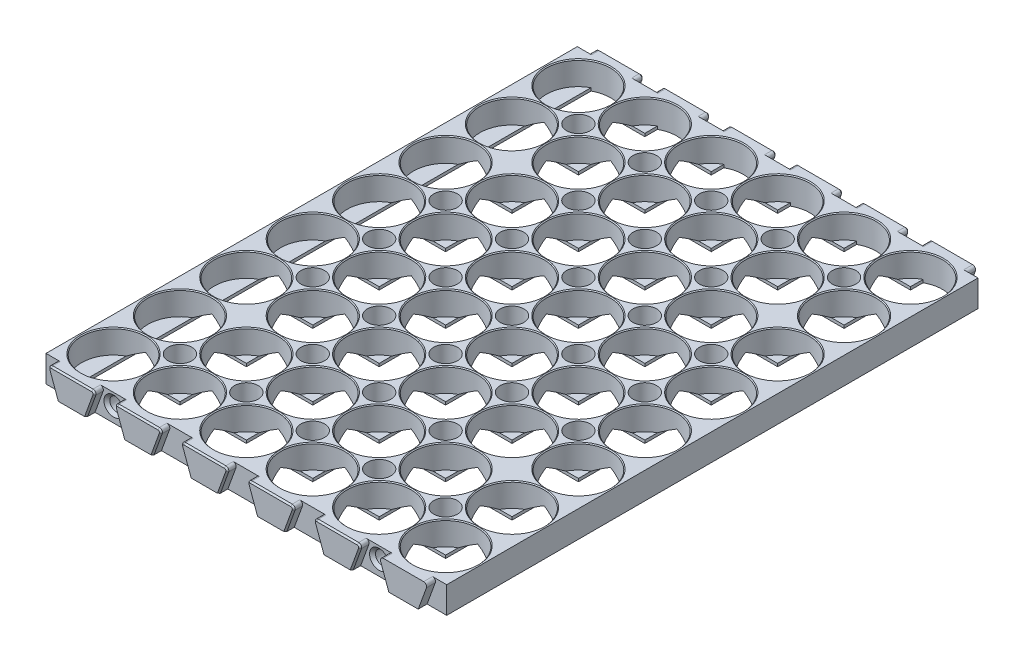
SolidWorks part; units mm, degrees
ref_plane "Front Plane" through (0, 0, 0) normal (0, 0, 1) x (1, 0, 0)
ref_plane "Top Plane" through (0, 0, 0) normal (0, 1, 0) x (1, 0, 0)
ref_plane "Right Plane" through (0, 0, 0) normal (1, 0, 0) x (0, 0, -1)
sketch "Sketch1" plane through (0, 0, 0) normal (0, 1, 0) x (1, 0, 0)
  line L0 (-11.25, 10.875) -> (11.25, 10.875) construction
  line L1 (-11.25, -11.25) -> (11.25, -11.25)
  line L2 (-11.25, -11.25) -> (-11.25, 11.25)
  line L3 (-11.25, 11.25) -> (11.25, 11.25)
  line L4 (11.25, -11.25) -> (11.25, 11.25)
  line L5 (-11.25, -11.25) -> (11.25, 11.25) construction
  line L6 (-11.25, 11.25) -> (11.25, -11.25) construction
  circle A0 centre (0, 0) radius 10.875
  point P0 (0, 0)
  dimension "D1" = 21.75
  dimension "D2" = 22.5
  dimension "D3" = 0.375
extrude "Boss-Extrude1" add sketch "Sketch1" along normal blind 8
sketch "Sketch2" plane through (0, 0, 0) normal (0, -1, 0) x (1, 0, 0)
  line L0 (5.25, 11.25) -> (-5.25, 11.25) construction
  line L1 (11.25, 11.25) -> (5.25, 11.25)
  line L2 (11.25, 11.25) -> (11.25, 5.25)
  line L3 (11.25, 5.25) -> (5.25, 5.25)
  line L4 (5.25, 11.25) -> (5.25, 5.25)
  line L5 (11.25, -11.25) -> (5.25, -11.25)
  line L6 (11.25, -11.25) -> (11.25, -5.25)
  line L7 (11.25, -5.25) -> (5.25, -5.25)
  line L8 (5.25, -11.25) -> (5.25, -5.25)
  line L9 (-11.25, -11.25) -> (-5.25, -11.25)
  line L10 (-11.25, -11.25) -> (-11.25, -5.25)
  line L11 (-11.25, -5.25) -> (-5.25, -5.25)
  line L12 (-5.25, -11.25) -> (-5.25, -5.25)
  line L13 (-11.25, 11.25) -> (-5.25, 11.25)
  line L14 (-11.25, 11.25) -> (-11.25, 5.25)
  line L15 (-11.25, 5.25) -> (-5.25, 5.25)
  line L16 (-5.25, 11.25) -> (-5.25, 5.25)
  line L17 (11.25, 5.25) -> (11.25, -5.25) construction
  line L18 (5.25, -11.25) -> (-5.25, -11.25) construction
  line L19 (-11.25, 5.25) -> (-11.25, -5.25) construction
  dimension "D1" = 10.5
extrude "Boss-Extrude2" add sketch "Sketch2" along normal blind 1
chamfer "Chamfer2" distance 0.3 angle 45 1 edges at (0, 8, 10.875)
pattern_linear "LPattern1" count 8 spacing 22.5 along (0, 0, 1) count 6 spacing 22.5 along (1, 0, 0) of "Boss-Extrude2", "Boss-Extrude1", "Chamfer2"
sketch "Sketch5" plane through (0, 0, -5.25) normal (0, 0, 1) x (1, 0, 0)
  line L25 (-5.25, -1) -> (-5.25, 0) construction
  line L26 (-5.25, -1) -> (-11.25, -1) construction
  line L27 (-11.25, -1) -> (-11.25, 0) construction
  line L29 (-5.25, 0) -> (-9.5238, 0) construction
  line L35 (-5.25, -1) -> (-5.25, 0)
  line L36 (-5.25, -1) -> (-11.25, -1)
  line L37 (-11.25, -1) -> (-11.25, 0)
  line L39 (-5.25, 0) -> (-11.25, 0)
  line L59 (123.75, -1) -> (117.75, -1)
  line L60 (123.75, -1) -> (123.75, 0)
  line L61 (123.75, 0) -> (117.75, 0)
  line L62 (117.75, -1) -> (117.75, 0)
  dimension "D1" = 6
extrude "Boss-Extrude3" add sketch "Sketch5" along normal up to surface (174 mm away)
sketch "Sketch6" plane through (0, 0, 0) normal (0, -1, 0) x (1, 0, 0)
  line L27 (39.75, -11.25) -> (50.25, -11.25) construction
  line L28 (50.25, -11.25) -> (50.25, -9.5238) construction
  line L29 (39.75, -9.5238) -> (39.75, -11.25) construction
  line L30 (17.25, -9.5238) -> (17.25, -11.25) construction
  line L31 (17.25, -11.25) -> (27.75, -11.25) construction
  line L32 (27.75, -11.25) -> (27.75, -9.5238) construction
  line L33 (-5.25, -9.5238) -> (-5.25, -11.25) construction
  line L34 (-5.25, -11.25) -> (5.25, -11.25) construction
  line L35 (5.25, -11.25) -> (5.25, -9.5238) construction
  line L51 (39.75, -11.25) -> (50.25, -11.25)
  line L52 (50.25, -11.25) -> (50.25, -9.5238)
  line L53 (39.75, -9.5238) -> (39.75, -11.25)
  line L54 (17.25, -9.5238) -> (17.25, -11.25)
  line L55 (17.25, -11.25) -> (27.75, -11.25)
  line L56 (27.75, -11.25) -> (27.75, -9.5238)
  line L57 (-5.25, -9.5238) -> (-5.25, -11.25)
  line L58 (-5.25, -11.25) -> (5.25, -11.25)
  line L59 (5.25, -11.25) -> (5.25, -9.5238)
  line L84 (5.25, 168.75) -> (-5.25, 168.75) construction
  line L85 (-5.25, 168.75) -> (-5.25, 167.0238) construction
  line L86 (5.25, 167.0238) -> (5.25, 168.75) construction
  line L87 (27.75, 167.0238) -> (27.75, 168.75) construction
  line L88 (27.75, 168.75) -> (17.25, 168.75) construction
  line L89 (17.25, 168.75) -> (17.25, 167.0238) construction
  line L93 (50.25, 167.0238) -> (50.25, 168.75) construction
  line L94 (50.25, 168.75) -> (39.75, 168.75) construction
  line L95 (39.75, 168.75) -> (39.75, 167.0238) construction
  line L96 (5.25, 168.75) -> (-5.25, 168.75)
  line L97 (-5.25, 168.75) -> (-5.25, 167.0238)
  line L98 (5.25, 167.0238) -> (5.25, 168.75)
  line L99 (27.75, 167.0238) -> (27.75, 168.75)
  line L100 (27.75, 168.75) -> (17.25, 168.75)
  line L101 (17.25, 168.75) -> (17.25, 167.0238)
  line L105 (50.25, 167.0238) -> (50.25, 168.75)
  line L106 (50.25, 168.75) -> (39.75, 168.75)
  line L107 (39.75, 168.75) -> (39.75, 167.0238)
  line L114 (72.75, 167.0238) -> (72.75, 168.75) construction
  line L115 (72.75, 168.75) -> (62.25, 168.75) construction
  line L116 (62.25, 168.75) -> (62.25, 167.0238) construction
  line L123 (72.75, 167.0238) -> (72.75, 168.75)
  line L124 (72.75, 168.75) -> (62.25, 168.75)
  line L125 (62.25, 168.75) -> (62.25, 167.0238)
  line L126 (117.75, 167.0238) -> (117.75, 168.75) construction
  line L127 (117.75, 168.75) -> (107.25, 168.75) construction
  line L128 (107.25, 168.75) -> (107.25, 167.0238) construction
  line L129 (62.25, -11.25) -> (72.75, -11.25)
  line L130 (72.75, -11.25) -> (72.75, -9.5238)
  line L131 (62.25, -9.5238) -> (62.25, -11.25)
  line L132 (62.25, -11.25) -> (72.75, -11.25)
  line L133 (72.75, -11.25) -> (72.75, -9.5238)
  line L134 (62.25, -9.5238) -> (62.25, -11.25)
  line L135 (95.25, 167.0238) -> (95.25, 168.75) construction
  line L136 (95.25, 168.75) -> (84.75, 168.75) construction
  line L137 (84.75, 168.75) -> (84.75, 167.0238) construction
  line L138 (107.25, -11.25) -> (117.75, -11.25) construction
  line L139 (117.75, -11.25) -> (117.75, -9.5238) construction
  line L140 (107.25, -9.5238) -> (107.25, -11.25) construction
  line L141 (84.75, -11.25) -> (95.25, -11.25) construction
  line L142 (95.25, -11.25) -> (95.25, -9.5238) construction
  line L143 (84.75, -9.5238) -> (84.75, -11.25) construction
  line L144 (117.75, 167.0238) -> (117.75, 168.75)
  line L145 (117.75, 168.75) -> (107.25, 168.75)
  line L146 (107.25, 168.75) -> (107.25, 167.0238)
  line L147 (95.25, 167.0238) -> (95.25, 168.75)
  line L148 (95.25, 168.75) -> (84.75, 168.75)
  line L149 (84.75, 168.75) -> (84.75, 167.0238)
  line L150 (107.25, -11.25) -> (117.75, -11.25)
  line L151 (117.75, -11.25) -> (117.75, -9.5238)
  line L152 (107.25, -9.5238) -> (107.25, -11.25)
  line L153 (84.75, -11.25) -> (95.25, -11.25)
  line L154 (95.25, -11.25) -> (95.25, -9.5238)
  line L155 (84.75, -9.5238) -> (84.75, -11.25)
  arc A9 (39.75, -9.5238) -> (50.25, -9.5238) centre (45, 0) ccw construction
  arc A10 (17.25, -9.5238) -> (27.75, -9.5238) centre (22.5, 0) ccw construction
  arc A11 (-5.25, -9.5238) -> (5.25, -9.5238) centre (0, 0) ccw construction
  arc A17 (39.75, -9.5238) -> (50.25, -9.5238) centre (45, 0) ccw
  arc A18 (17.25, -9.5238) -> (27.75, -9.5238) centre (22.5, 0) ccw
  arc A19 (-5.25, -9.5238) -> (5.25, -9.5238) centre (0, 0) ccw
  arc A28 (5.25, 167.0238) -> (-5.25, 167.0238) centre (0, 157.5) ccw construction
  arc A29 (27.75, 167.0238) -> (17.25, 167.0238) centre (22.5, 157.5) ccw construction
  arc A31 (50.25, 167.0238) -> (39.75, 167.0238) centre (45, 157.5) ccw construction
  arc A32 (5.25, 167.0238) -> (-5.25, 167.0238) centre (0, 157.5) ccw
  arc A33 (27.75, 167.0238) -> (17.25, 167.0238) centre (22.5, 157.5) ccw
  arc A35 (50.25, 167.0238) -> (39.75, 167.0238) centre (45, 157.5) ccw
  arc A38 (72.75, 167.0238) -> (62.25, 167.0238) centre (67.5, 157.5) ccw construction
  arc A41 (72.75, 167.0238) -> (62.25, 167.0238) centre (67.5, 157.5) ccw
  arc A42 (117.75, 167.0238) -> (107.25, 167.0238) centre (112.5, 157.5) ccw construction
  arc A43 (62.25, -9.5238) -> (72.75, -9.5238) centre (67.5, 0) ccw
  arc A44 (62.25, -9.5238) -> (72.75, -9.5238) centre (67.5, 0) ccw
  arc A45 (95.25, 167.0238) -> (84.75, 167.0238) centre (90, 157.5) ccw construction
  arc A46 (107.25, -9.5238) -> (117.75, -9.5238) centre (112.5, 0) ccw construction
  arc A47 (84.75, -9.5238) -> (95.25, -9.5238) centre (90, 0) ccw construction
  arc A48 (117.75, 167.0238) -> (107.25, 167.0238) centre (112.5, 157.5) ccw
  arc A49 (95.25, 167.0238) -> (84.75, 167.0238) centre (90, 157.5) ccw
  arc A50 (107.25, -9.5238) -> (117.75, -9.5238) centre (112.5, 0) ccw
  arc A51 (84.75, -9.5238) -> (95.25, -9.5238) centre (90, 0) ccw
  dimension "D1" = 0
extrude "Boss-Extrude4" add sketch "Sketch6" along normal up to surface (1 mm away) up to face at (-8.25, -1, 78.75)
sketch "Sketch7" plane through (0, 0, 0) normal (0, 0, 1) x (1, 0, 0)
  line L0 (-11.25, 8) -> (123.75, 8) construction
  line L1 (-5.25, 0) -> (5.25, 0)
  line L2 (-5.25, 0) -> (0, 5.25) construction
  line L3 (0, 5.25) -> (5.25, 0) construction
  line L4 (0, 0) -> (0, 8) construction
  line L5 (84.75, 0) -> (90, 3.0311)
  line L6 (-5.25, 0) -> (0, 3.0311)
  line L7 (0, 3.0311) -> (5.25, 0)
  line L8 (90, 3.0311) -> (95.25, 0)
  line L9 (-5.25, -1) -> (-5.25, 0) construction
  line L10 (5.25, -1) -> (5.25, 0) construction
  line L11 (-5.25, -1) -> (-5.25, 0) construction
  line L12 (5.25, -1) -> (5.25, 0) construction
  line L13 (17.25, 0) -> (22.5, 3.0311)
  line L14 (22.5, 3.0311) -> (27.75, 0)
  line L15 (17.25, 0) -> (27.75, 0)
  line L16 (39.75, 0) -> (45, 3.0311)
  line L17 (45, 3.0311) -> (50.25, 0)
  line L18 (39.75, 0) -> (50.25, 0)
  line L19 (62.25, 0) -> (67.5, 3.0311)
  line L20 (67.5, 3.0311) -> (72.75, 0)
  line L21 (62.25, 0) -> (72.75, 0)
  line L22 (-5.25, 0) -> (17.25, 0) construction
  line L23 (84.75, 0) -> (95.25, 0)
  line L24 (107.25, 0) -> (112.5, 3.0311)
  line L25 (112.5, 3.0311) -> (117.75, 0)
  line L26 (107.25, 0) -> (117.75, 0)
  dimension "D1" = 45
  dimension "D2" = 30
  dimension "D3" = 4.9689
  dimension "D5" = 22.5
  dimension "D4" = 6
extrude "Cut-Extrude1" cut sketch "Sketch7" along normal up to surface (162.75 mm away) up to face at (56.25, -0.3333, 162.75)
sketch "Sketch16" plane through (0, 0, 0) normal (1, 0, 0) x (0, 0, -1)
  line L2 (-5.25, -1) -> (-5.25, 0) construction
  line L3 (5.25, -1) -> (5.25, 0) construction
  line L4 (-5.25, 0) -> (0, 3.0311)
  line L5 (0, 3.0311) -> (5.25, 0)
  line L6 (-5.25, 0) -> (5.25, 0)
  line L7 (-5.25, -1) -> (-5.25, 0) construction
  line L8 (5.25, -1) -> (5.25, 0) construction
  line L9 (-22.5, 3.0311) -> (-17.25, 0)
  line L10 (-27.75, 0) -> (-17.25, 0)
  line L11 (-27.75, 0) -> (-22.5, 3.0311)
  line L12 (-45, 3.0311) -> (-39.75, 0)
  line L13 (-50.25, 0) -> (-39.75, 0)
  line L14 (-50.25, 0) -> (-45, 3.0311)
  line L15 (-67.5, 3.0311) -> (-62.25, 0)
  line L16 (-72.75, 0) -> (-62.25, 0)
  line L17 (-72.75, 0) -> (-67.5, 3.0311)
  line L18 (-90, 3.0311) -> (-84.75, 0)
  line L19 (-95.25, 0) -> (-84.75, 0)
  line L20 (-95.25, 0) -> (-90, 3.0311)
  line L21 (-112.5, 3.0311) -> (-107.25, 0)
  line L22 (-117.75, 0) -> (-107.25, 0)
  line L23 (-117.75, 0) -> (-112.5, 3.0311)
  line L24 (-135, 3.0311) -> (-129.75, 0)
  line L25 (-140.25, 0) -> (-129.75, 0)
  line L26 (-140.25, 0) -> (-135, 3.0311)
  line L27 (-157.5, 3.0311) -> (-152.25, 0)
  line L28 (-162.75, 0) -> (-152.25, 0)
  line L29 (-162.75, 0) -> (-157.5, 3.0311)
  line L42 (0, 3.0311) -> (-22.5, 3.0311) construction
  dimension "D1" = 30
  dimension "D3" = 22.5
  dimension "D2" = 8
extrude "Cut-Extrude7" cut sketch "Sketch16" along normal up to surface (107.25 mm away)
sketch "Sketch8" plane through (0, 0, -11.25) normal (0, 0, -1) x (-1, 0, 0)
  line L0 (0, -1) -> (0, 8) construction
  line L1 (-27.4743, -1) -> (-30.75, 8)
  line L2 (-123.75, 8) -> (11.25, 8) construction
  line L3 (4.9743, -1) -> (-4.9743, -1)
  line L4 (-4.9743, -1) -> (-8.25, 8)
  line L5 (-8.25, 8) -> (8.25, 8)
  line L6 (4.9743, -1) -> (8.25, 8)
  line L7 (11.25, 8) -> (11.25, -1) construction
  line L8 (11.25, -1) -> (-123.75, -1) construction
  line L9 (-30.75, 8) -> (-14.25, 8)
  line L10 (-123.75, 8) -> (11.25, 8) construction
  line L11 (-17.5257, -1) -> (-14.25, 8)
  line L12 (-17.5257, -1) -> (-27.4743, -1)
  line L13 (-49.9743, -1) -> (-53.25, 8)
  line L14 (-53.25, 8) -> (-36.75, 8)
  line L15 (-40.0257, -1) -> (-36.75, 8)
  line L16 (-40.0257, -1) -> (-49.9743, -1)
  line L17 (-72.4743, -1) -> (-75.75, 8)
  line L18 (-75.75, 8) -> (-59.25, 8)
  line L19 (-62.5257, -1) -> (-59.25, 8)
  line L20 (-62.5257, -1) -> (-72.4743, -1)
  line L21 (-4.9743, -1) -> (-27.4743, -1) construction
  line L22 (-123.75, 8) -> (11.25, 8) construction
  line L23 (-94.9743, -1) -> (-98.25, 8)
  line L24 (-98.25, 8) -> (-81.75, 8)
  line L25 (-85.0257, -1) -> (-81.75, 8)
  line L26 (-85.0257, -1) -> (-94.9743, -1)
  line L27 (-117.4743, -1) -> (-120.75, 8)
  line L28 (-120.75, 8) -> (-104.25, 8)
  line L29 (-107.5257, -1) -> (-104.25, 8)
  line L30 (-107.5257, -1) -> (-117.4743, -1)
  dimension "D1" = 70
  dimension "D2" = 3
  dimension "D4" = 22.5
  dimension "D5" = 9
  dimension "D3" = 6
sketch "Sketch9" plane through (0, 0, 168.75) normal (0, 0, 1) x (1, 0, 0)
  line L0 (85.0257, -1) -> (94.9743, -1) construction
  line L3 (85.0257, -1) -> (81.75, 8) construction
  line L20 (94.9743, -1) -> (98.25, 8) construction
  line L21 (98.25, 8) -> (81.75, 8) construction
  line L22 (85.0257, -1) -> (94.9743, -1)
  line L23 (85.0257, -1) -> (81.75, 8)
  line L24 (-4.9743, -1) -> (4.9743, -1)
  line L25 (4.9743, -1) -> (8.25, 8)
  line L26 (8.25, 8) -> (-8.25, 8)
  line L27 (-8.25, 8) -> (-4.9743, -1)
  line L28 (-4.9743, -1) -> (4.9743, -1)
  line L29 (4.9743, -1) -> (8.25, 8)
  line L30 (8.25, 8) -> (-8.25, 8)
  line L31 (-8.25, 8) -> (-4.9743, -1)
  line L32 (72.4743, -1) -> (75.75, 8)
  line L33 (75.75, 8) -> (59.25, 8)
  line L34 (59.25, 8) -> (62.5257, -1)
  line L35 (62.5257, -1) -> (72.4743, -1)
  line L36 (72.4743, -1) -> (75.75, 8)
  line L37 (75.75, 8) -> (59.25, 8)
  line L38 (59.25, 8) -> (62.5257, -1)
  line L39 (62.5257, -1) -> (72.4743, -1)
  line L40 (49.9743, -1) -> (53.25, 8)
  line L41 (53.25, 8) -> (36.75, 8)
  line L42 (36.75, 8) -> (40.0257, -1)
  line L43 (40.0257, -1) -> (49.9743, -1)
  line L44 (49.9743, -1) -> (53.25, 8)
  line L45 (53.25, 8) -> (36.75, 8)
  line L46 (36.75, 8) -> (40.0257, -1)
  line L47 (40.0257, -1) -> (49.9743, -1)
  line L48 (14.25, 8) -> (17.5257, -1)
  line L49 (17.5257, -1) -> (27.4743, -1)
  line L50 (27.4743, -1) -> (30.75, 8)
  line L51 (30.75, 8) -> (14.25, 8)
  line L52 (14.25, 8) -> (17.5257, -1)
  line L53 (17.5257, -1) -> (27.4743, -1)
  line L54 (27.4743, -1) -> (30.75, 8)
  line L55 (30.75, 8) -> (14.25, 8)
  line L56 (94.9743, -1) -> (98.25, 8)
  line L57 (98.25, 8) -> (81.75, 8)
  line L58 (107.5257, -1) -> (117.4743, -1) construction
  line L59 (107.5257, -1) -> (104.25, 8) construction
  line L60 (117.4743, -1) -> (120.75, 8) construction
  line L61 (120.75, 8) -> (104.25, 8) construction
  line L62 (107.5257, -1) -> (117.4743, -1)
  line L63 (107.5257, -1) -> (104.25, 8)
  line L64 (117.4743, -1) -> (120.75, 8)
  line L65 (120.75, 8) -> (104.25, 8)
  dimension "D1" = 0
  dimension "D2" = 0
  dimension "D3" = 0
  dimension "D4" = 0
extrude "Boss-Extrude5" add sketch "Sketch8" along normal blind 3
extrude "Boss-Extrude6" add sketch "Sketch9" along normal blind 3
fillet "Fillet1" radius 1 24 edges at (-8.25, 8, -12.75) (8.25, 8, -12.75) (14.25, 8, -12.75) (59.25, 8, -12.75) (53.25, 8, -12.75) (30.75, 8, -12.75) (36.75, 8, -12.75) (75.75, 8, -12.75) (81.75, 8, -12.75) (98.25, 8, -12.75) (104.25, 8, -12.75) (120.75, 8, -12.75) (-8.25, 8, 170.25) (8.25, 8, 170.25) (14.25, 8, 170.25) (30.75, 8, 170.25) (36.75, 8, 170.25) (53.25, 8, 170.25) (59.25, 8, 170.25) (75.75, 8, 170.25) (81.75, 8, 170.25) (98.25, 8, 170.25) (104.25, 8, 170.25) (120.75, 8, 170.25)
chamfer "Chamfer3" distance 0.5 angle 45 50 edges at (6.3679, 2.829, -14.25) (0, 8, -14.25) (-6.3679, 2.829, -14.25) (73.8679, 2.829, -14.25) (67.5, 8, -14.25) (61.1321, 2.829, -14.25) (51.3679, 2.829, -14.25) (45, 8, -14.25) (38.6321, 2.829, -14.25) (28.8679, 2.829, -14.25) (22.5, 8, -14.25) (16.1321, 2.829, -14.25) (73.8679, 2.829, 171.75) (61.1321, 2.829, 171.75) (67.5, 8, 171.75) (51.3679, 2.829, 171.75) (38.6321, 2.829, 171.75) (45, 8, 171.75) (28.8679, 2.829, 171.75) (16.1321, 2.829, 171.75) (22.5, 8, 171.75) (6.3679, 2.829, 171.75) (-6.3679, 2.829, 171.75) (0, 8, 171.75) (83.6321, 2.829, -14.25) (90, 8, -14.25) (96.3679, 2.829, -14.25) (96.3679, 2.829, 171.75) (90, 8, 171.75) (83.6321, 2.829, 171.75) (82.359, 7.5736, -14.25) (97.641, 7.5736, -14.25) (97.641, 7.5736, 171.75) (82.359, 7.5736, 171.75) (75.141, 7.5736, 171.75) (59.859, 7.5736, 171.75) (52.641, 7.5736, 171.75) (37.359, 7.5736, 171.75) (30.141, 7.5736, 171.75) (14.859, 7.5736, 171.75) (7.641, 7.5736, 171.75) (-7.641, 7.5736, 171.75) (75.141, 7.5736, -14.25) (59.859, 7.5736, -14.25) (52.641, 7.5736, -14.25) (37.359, 7.5736, -14.25) (30.141, 7.5736, -14.25) (14.859, 7.5736, -14.25) (7.641, 7.5736, -14.25) (-7.641, 7.5736, -14.25)
sketch "Sketch10" plane through (0, 0, -11.25) normal (0, 0, -1) x (-1, 0, 0)
  line L0 (-11.25, -1) -> (-11.25, 8) construction
  line L2 (-4.9743, -1) -> (-17.5257, -1) construction
  line L4 (-14.25, 8) -> (-8.25, 8) construction
  line L5 (-56.25, 8) -> (-56.25, -1) construction
  line L6 (-49.9743, -1) -> (-62.5257, -1) construction
  line L7 (-59.25, 8) -> (-53.25, 8) construction
  circle A0 centre (-11.25, 4) radius 2.25
  circle A1 centre (-101.25, 4) radius 2.25
  dimension "D2" = 4.5
  dimension "D1" = 4
sketch "Sketch11" plane through (0, 0, 168.75) normal (0, 0, 1) x (1, 0, 0)
  circle A0 centre (11.25, 4) radius 2.25 construction
  circle A1 centre (11.25, 4) radius 2.25
  circle A2 centre (101.25, 4) radius 2.25 construction
  circle A3 centre (101.25, 4) radius 2.25
extrude "Cut-Extrude2" cut sketch "Sketch10" against normal blind 5
extrude "Cut-Extrude3" cut sketch "Sketch11" against normal blind 5
chamfer "Chamfer5" distance 1 angle 45 4 edges at (103.5, 4, -11.25) (9, 4, -11.25) (13.5, 4, 168.75) (103.5, 4, 168.75)
sketch "Sketch17" plane through (0, -1, 0) normal (0, -1, 0) x (1, 0, 0)
  line L0 (5.25, 5.25) -> (17.25, 17.25) construction
  line L1 (11.25, 11.25) -> (33.75, 11.25) construction
  line L2 (95.25, 140.25) -> (107.25, 152.25) construction
  line L3 (17.25, 140.25) -> (5.25, 152.25) construction
  circle A0 centre (11.25, 11.25) radius 4
  circle A1 centre (33.75, 11.25) radius 4
  circle A2 centre (56.25, 11.25) radius 4
  circle A33 centre (33.75, 146.25) radius 4 [skipped]
  circle A34 centre (56.25, 146.25) radius 4 [skipped]
  circle A35 centre (33.75, 168.75) radius 4 [skipped]
  circle A36 centre (33.75, 191.25) radius 4 [skipped]
  circle A37 centre (56.25, 191.25) radius 4 [skipped]
  circle A38 centre (33.75, 213.75) radius 4 [skipped]
  circle A39 centre (56.25, 213.75) radius 4 [skipped]
  circle A40 centre (33.75, 236.25) radius 4 [skipped]
  circle A41 centre (56.25, 236.25) radius 4 [skipped]
  circle A42 centre (11.25, 146.25) radius 4 [skipped]
  circle A43 centre (11.25, 191.25) radius 4 [skipped]
  circle A44 centre (11.25, 213.75) radius 4 [skipped]
  circle A45 centre (11.25, 236.25) radius 4 [skipped]
  circle A46 centre (56.25, 168.75) radius 4 construction
  circle A47 centre (11.25, 168.75) radius 4 construction
  circle A48 centre (33.75, 123.75) radius 4 [skipped]
  circle A49 centre (56.25, 123.75) radius 4 [skipped]
  circle A50 centre (11.25, 123.75) radius 4 [skipped]
  circle A57 centre (33.75, 33.75) radius 4 [skipped]
  circle A58 centre (33.75, 56.25) radius 4 [skipped]
  circle A59 centre (56.25, 56.25) radius 4 [skipped]
  circle A60 centre (33.75, 78.75) radius 4 [skipped]
  circle A61 centre (56.25, 78.75) radius 4 [skipped]
  circle A62 centre (33.75, 101.25) radius 4 [skipped]
  circle A63 centre (56.25, 101.25) radius 4 [skipped]
  circle A64 centre (11.25, 56.25) radius 4 [skipped]
  circle A65 centre (11.25, 78.75) radius 4 [skipped]
  circle A66 centre (11.25, 101.25) radius 4 [skipped]
  circle A67 centre (56.25, 33.75) radius 4 construction
  circle A68 centre (11.25, 33.75) radius 4 construction
  circle A69 centre (11.25, 33.75) radius 4 construction
  circle A70 centre (33.75, 33.75) radius 4
  circle A71 centre (56.25, 33.75) radius 4
  circle A72 centre (11.25, 56.25) radius 4
  circle A73 centre (33.75, 56.25) radius 4
  circle A74 centre (56.25, 56.25) radius 4
  circle A75 centre (11.25, 78.75) radius 4
  circle A76 centre (33.75, 78.75) radius 4
  circle A77 centre (56.25, 78.75) radius 4
  circle A78 centre (11.25, 101.25) radius 4
  circle A79 centre (33.75, 101.25) radius 4
  circle A80 centre (56.25, 101.25) radius 4
  circle A81 centre (11.25, 123.75) radius 4 construction
  circle A82 centre (33.75, 123.75) radius 4
  circle A83 centre (56.25, 123.75) radius 4
  circle A84 centre (11.25, 146.25) radius 4
  circle A85 centre (33.75, 146.25) radius 4
  circle A86 centre (56.25, 146.25) radius 4
  circle A87 centre (11.25, 258.75) radius 4 [skipped]
  circle A88 centre (33.75, 258.75) radius 4 [skipped]
  circle A89 centre (56.25, 258.75) radius 4 [skipped]
  circle A90 centre (11.25, 281.25) radius 4 [skipped]
  circle A91 centre (33.75, 281.25) radius 4 [skipped]
  circle A92 centre (56.25, 281.25) radius 4 [skipped]
  circle A93 centre (78.75, 11.25) radius 4
  circle A94 centre (78.75, 33.75) radius 4
  circle A95 centre (78.75, 56.25) radius 4
  circle A96 centre (78.75, 78.75) radius 4
  circle A97 centre (78.75, 101.25) radius 4
  circle A98 centre (78.75, 123.75) radius 4
  circle A99 centre (78.75, 146.25) radius 4
  circle A106 centre (78.75, 168.75) radius 4 [skipped]
  circle A107 centre (78.75, 191.25) radius 4 [skipped]
  circle A108 centre (78.75, 213.75) radius 4 [skipped]
  circle A109 centre (78.75, 236.25) radius 4 [skipped]
  circle A110 centre (78.75, 258.75) radius 4 [skipped]
  circle A111 centre (78.75, 281.25) radius 4 [skipped]
  circle A112 centre (101.25, 11.25) radius 4
  circle A113 centre (101.25, 33.75) radius 4 construction
  circle A114 centre (101.25, 56.25) radius 4
  circle A115 centre (101.25, 78.75) radius 4
  circle A116 centre (101.25, 101.25) radius 4
  circle A117 centre (101.25, 123.75) radius 4 construction
  circle A118 centre (101.25, 146.25) radius 4
  circle A126 centre (101.25, 191.25) radius 4 [skipped]
  circle A127 centre (101.25, 213.75) radius 4 [skipped]
  circle A128 centre (101.25, 236.25) radius 4 [skipped]
  circle A129 centre (101.25, 258.75) radius 4 [skipped]
  circle A130 centre (101.25, 281.25) radius 4 [skipped]
  circle A131 centre (101.25, 168.75) radius 4 [skipped]
  dimension "D4" = 22.5
  dimension "D1" = 8
  dimension "D2" = 5
  dimension "D3" = 13
  dimension "D5" = 7
extrude "Cut-Extrude8" cut sketch "Sketch17" against normal through all
sketch "Sketch18" plane through (0, -1, 0) normal (0, -1, 0) x (1, 0, 0)
  line L0 (123.75, -11.25) -> (123.75, 168.75) construction
  line L1 (107.25, 117.75) -> (107.25, 129.75) construction
  line L2 (5.25, 117.75) -> (17.25, 129.75) construction
  line L3 (5.25, 27.75) -> (17.25, 39.75) construction
  line L4 (95.25, 27.75) -> (107.25, 39.75) construction
  line L7 (95.25, 129.75) -> (95.25, 117.75) construction
  line L8 (107.25, 129.75) -> (95.25, 129.75) construction
  line L38 (123.75, 78.75) -> (-11.25, 78.75) construction
  line L40 (-11.25, 168.75) -> (-11.25, -11.25) construction
  line L42 (95.25, 129.75) -> (107.25, 117.75) construction
  circle A0 centre (11.25, 33.75) radius 2.1
  circle A4 centre (101.25, 33.75) radius 2.1
  circle A7 centre (101.25, 123.75) radius 2.1
  circle A8 centre (11.25, 123.75) radius 2.1
  dimension "D1" = 4.2
extrude "Cut-Extrude9" cut sketch "Sketch18" against normal blind 4
sketch "Sketch19" plane through (0, -1, 0) normal (0, -1, 0) x (1, 0, 0)
  line L0 (123.75, 78.75) -> (-11.25, 78.75) construction
  line L1 (123.75, -11.25) -> (123.75, 168.75) construction
  line L2 (-11.25, 168.75) -> (-11.25, -11.25) construction
  circle A2 centre (101.25, 123.75) radius 1.7
  circle A3 centre (11.25, 33.75) radius 1.7
  circle A4 centre (11.25, 123.75) radius 1.7
  circle A5 centre (101.25, 33.75) radius 1.7
  dimension "D1" = 3.4
extrude "Cut-Extrude10" cut sketch "Sketch19" against normal offset from surface (7 mm away) 2
chamfer "Chamfer6" distance 1 angle 45 4 edges at (11.25, -1, 121.65) (11.25, -1, 31.65) (101.25, -1, 31.65) (101.25, -1, 121.65)
sketch "Sketch22" plane through (0, 8, 0) normal (0, 1, 0) x (1, 0, 0)
  line L0 (-11.25, -168.75) -> (-6.8219, -168.75) construction
  line L1 (-11.25, 11.25) -> (-11.625, 11.25)
  line L2 (-11.25, 11.25) -> (-11.25, -168.75)
  line L3 (-11.25, -168.75) -> (-11.625, -168.75)
  line L4 (-11.625, 11.25) -> (-11.625, -168.75)
  line L5 (56.25, 11.25) -> (56.25, -168.75) construction
  line L6 (53.25, -168.75) -> (59.25, -168.75) construction
  line L7 (59.25, 11.25) -> (53.25, 11.25) construction
  line L14 (124.125, 11.25) -> (124.125, -168.75)
  line L15 (123.75, -168.75) -> (124.125, -168.75)
  line L16 (123.75, 11.25) -> (123.75, -168.75)
  line L17 (123.75, 11.25) -> (124.125, 11.25)
  arc A1 (-5.25, 9.5238) -> (-5.25, -9.5238) centre (0, 0) ccw construction
  point P10 (-10.875, 0)
  dimension "D1" = 0.75
  dimension "D2" = 0.375
extrude "Boss-Extrude7" add sketch "Sketch22" against normal up to surface (9 mm away)
sketch "Sketch14" plane through (0, -1, 0) normal (0, -1, 0) x (1, 0, 0)
  line L0 (-10.25, 76.2941) -> (-10.25, 81.2059)
  line L2 (-10.25, 78.75) -> (-11.625, 78.75) construction
  line L4 (56.25, -11.25) -> (56.25, 168.75) construction
  line L19 (-11.625, -11.25) -> (-11.625, 168.75) construction
  line L39 (-6.25, 77.75) -> (-6.25, 79.75)
  line L40 (-10.25, 8.7941) -> (-10.25, 13.7059)
  line L51 (-6.25, 10.25) -> (-6.25, 12.25)
  line L52 (-5.25, 146.25) -> (-6.25, 146.25) construction
  line L54 (-10.25, 13.7059) -> (-6.25, 12.25)
  line L55 (-6.25, 146.25) -> (-10.25, 146.25) construction
  line L56 (-10.25, 146.25) -> (-11.625, 146.25) construction
  line L57 (-10.25, 81.2059) -> (-6.25, 79.75)
  line L58 (-5.25, -9.5238) -> (-5.25, 167.0238) construction
  line L59 (-10.25, 148.7059) -> (-6.25, 147.25)
  line L60 (-10.25, 143.7941) -> (-6.25, 145.25)
  line L61 (-6.25, 147.25) -> (-6.25, 145.25)
  line L62 (-10.25, 148.7059) -> (-10.25, 143.7941)
  line L64 (117.75, 78.75) -> (118.75, 78.75) construction
  line L65 (118.75, 78.75) -> (122.75, 78.75) construction
  line L66 (117.75, 11.25) -> (118.75, 11.25) construction
  line L67 (118.75, 11.25) -> (122.75, 11.25) construction
  line L68 (-5.25, 9.5238) -> (-5.25, 12.9762) construction
  line L69 (-10.25, 11.25) -> (-11.625, 11.25) construction
  line L70 (-6.25, 11.25) -> (-10.25, 11.25) construction
  line L71 (-5.25, 11.25) -> (-6.25, 11.25) construction
  line L75 (-10.25, 8.7941) -> (-6.25, 10.25)
  line L76 (122.75, 11.25) -> (124.125, 11.25) construction
  line L77 (122.75, 146.25) -> (124.125, 146.25) construction
  line L78 (118.75, 146.25) -> (122.75, 146.25) construction
  line L79 (117.75, 146.25) -> (118.75, 146.25) construction
  line L84 (122.75, 78.75) -> (124.125, 78.75) construction
  line L85 (122.75, 76.2941) -> (118.75, 77.75)
  line L86 (122.75, 8.7941) -> (118.75, 10.25)
  line L87 (122.75, 148.7059) -> (122.75, 143.7941)
  line L93 (118.75, 147.25) -> (118.75, 145.25)
  line L94 (-6.25, 78.75) -> (-10.25, 78.75) construction
  line L95 (-5.25, 78.75) -> (-6.25, 78.75) construction
  line L98 (-10.25, 76.2941) -> (-6.25, 77.75)
  line L99 (122.75, 143.7941) -> (118.75, 145.25)
  line L100 (122.75, 148.7059) -> (118.75, 147.25)
  line L101 (122.75, 81.2059) -> (118.75, 79.75)
  line L102 (122.75, 13.7059) -> (118.75, 12.25)
  line L103 (118.75, 10.25) -> (118.75, 12.25)
  line L104 (122.75, 8.7941) -> (122.75, 13.7059)
  line L105 (118.75, 77.75) -> (118.75, 79.75)
  line L106 (122.75, 76.2941) -> (122.75, 81.2059)
  line L107 (62.5257, 168.75) -> (49.9743, 168.75) construction
  line L108 (49.9743, -11.25) -> (62.5257, -11.25) construction
  point P59 (118.75, 78.75)
  dimension "D1" = 70
  dimension "D2" = 4
  dimension "D3" = 1
  dimension "D4" = 4
  dimension "D5" = 1.375
  dimension "D8" = 2.4559
  dimension "D9" = 1
extrude "Cut-Extrude11" cut sketch "Sketch14" against normal blind 2
chamfer "Chamfer7" distance 0.5 angle 45 24 edges at (118.75, -1, 146.25) (120.75, -1, 144.5221) (122.75, -1, 146.25) (120.75, -1, 147.9779) (-10.25, -1, 146.25) (-8.25, -1, 144.5221) (-6.25, -1, 146.25) (-8.25, -1, 147.9779) (-6.25, -1, 78.75) (-8.25, -1, 77.0221) (-10.25, -1, 78.75) (-8.25, -1, 80.4779) (118.75, -1, 78.75) (120.75, -1, 77.0221) (122.75, -1, 78.75) (120.75, -1, 80.4779) (118.75, -1, 11.25) (120.75, -1, 9.5221) (122.75, -1, 11.25) (120.75, -1, 12.9779) (-10.25, -1, 11.25) (-8.25, -1, 12.9779) (-6.25, -1, 11.25) (-8.25, -1, 9.5221)
equation "\"cell_side\"= 22.50"
equation "\"D2@Sketch1\"=\"cell_side\""
equation "\"D5@Sketch7\"=\"cell_side\""
equation "\"D3@Sketch16\"=\"cell_side\""
equation "\"D4@Sketch8\"=\"cell_side\""
equation "\"D3@LPattern1\"=\"cell_side\""
equation "\"D4@LPattern1\"=\"cell_side\""
equation "\"D4@Sketch17\"=\"cell_side\""
